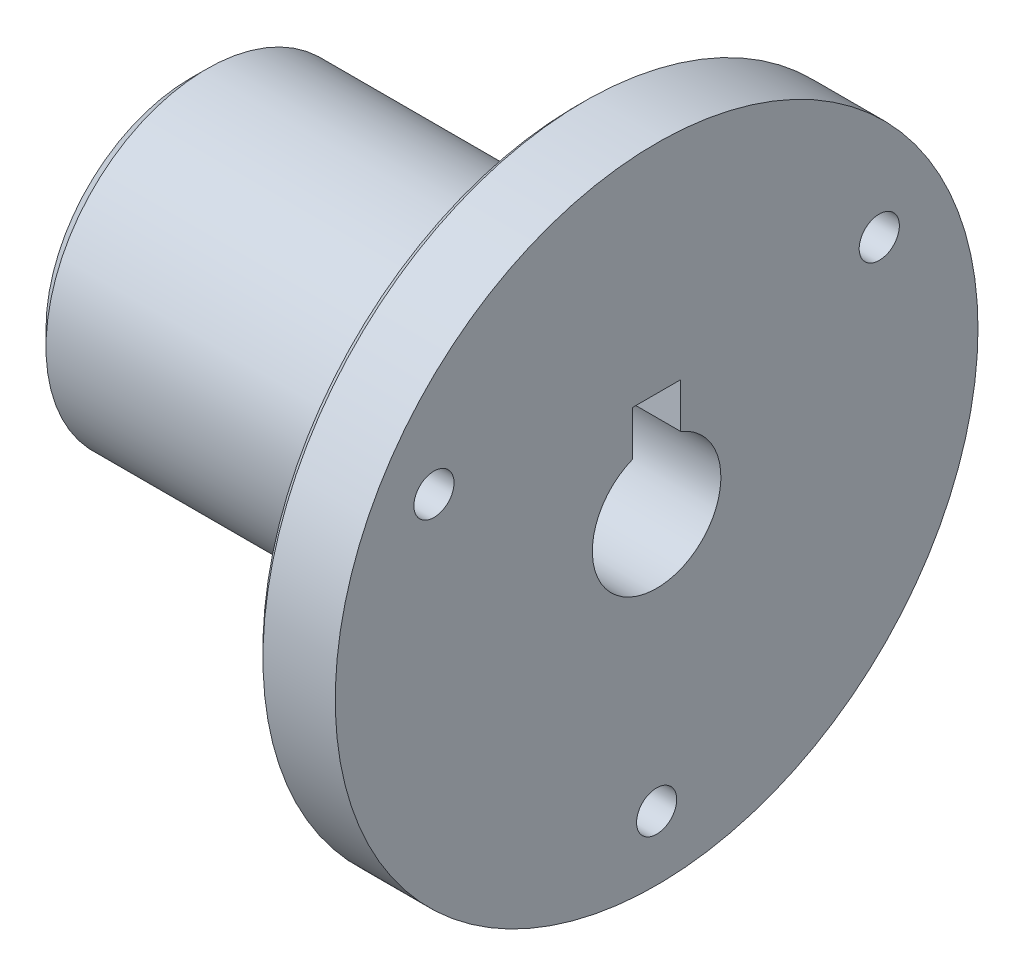
SolidWorks part; units mm, degrees
ref_plane "Front" through (0, 0, 0) normal (0, 0, 1) x (1, 0, 0)
ref_plane "Top" through (0, 0, 0) normal (0, 1, 0) x (1, 0, 0)
ref_plane "Right" through (0, 0, 0) normal (1, 0, 0) x (0, 0, -1)
sketch "草图1" plane through (0, 0, 0) normal (1, 0, 0) x (0, 0, -1)
  line L0 (-1.5, 6) -> (-1.5, 6.5)
  line L1 (0, 6) -> (-1.5, 6) construction
  line L2 (-1.5, 6) -> (-1.5, 3.7081)
  line L3 (0, 6) -> (1.5, 6) construction
  line L4 (1.5, 6) -> (1.5, 3.7081)
  line L5 (-1.5, 6.5) -> (1.5, 6.5)
  line L6 (1.5, 6.5) -> (1.5, 6)
  arc A0 (-1.5, 3.7081) -> (1.5, 3.7081) centre (0, 0) ccw
  circle A1 centre (0, 0) radius 10
extrude "凸台-拉伸1" add sketch "草图1" along normal blind 24
sketch "草图2" plane through (24, 0, 0) normal (1, 0, 0) x (0, 0, -1)
  line L0 (0, 0) -> (13.8564, 8) construction
  line L1 (0, 0) -> (-13.8564, 8) construction
  line L2 (0, 0) -> (0, -16) construction
  circle A0 centre (0, 0) radius 16 construction
  circle A1 centre (0, 0) radius 20
extrude "凸台-拉伸2" add sketch "草图2" along normal blind 5
hole_wizard "M3x0.5 螺纹孔1" positions "草图3" profile "草图4" tap size "M3x0.5" standard "ANSI Metric"
sketch "草图3" plane through (29, 0, 0) normal (1, 0, 0) x (0, 0, -1)
  point P0 (-13.8564, 8)
  point P3 (13.8564, 8)
  point P6 (0, -16)
sketch "草图4" plane through (29, 8, 13.8564) normal (0, 1, 0) x (0, 0, -1)
  line L0 (0, 0) -> (0, 8.2511)
  line L1 (0, 8.2511) -> (1.25, 7.5)
  line L2 (1.25, 7.5) -> (1.25, 0)
  line L5 (1.25, 0) -> (0, 0)
  line L10 (0, 8.2511) -> (-1.25, 7.5) construction
  line L11 (0, -6.35) -> (0, 107.95) construction
  dimension "螺纹孔钻头直径" = 2.5
  dimension "螺纹孔钻头深度" = 7.5
  dimension "导头角度" = 118
cosmetic thread "孔螺蚊线1" parameters "D1"=6, "D2"=3
cosmetic thread "孔螺蚊线2" parameters "D1"=6, "D2"=3
cosmetic thread "孔螺蚊线3" parameters "D1"=6, "D2"=3
sketch "草图5" plane through (29, 0, 0) normal (1, 0, 0) x (0, 0, -1)
  line L0 (-1.5, 6.5) -> (-1.5, 3.7081)
  line L1 (-1.5, 6.5) -> (1.5, 6.5)
  line L2 (1.5, 6.5) -> (1.5, 3.7081)
  arc A0 (-1.5, 3.7081) -> (1.5, 3.7081) centre (0, 0) ccw
extrude "切除-拉伸1" cut sketch "草图5" against normal up to next
chamfer "倒角1" distance 0.5 angle 45 1 edges at (0, -4, 0)
chamfer "倒角2" distance 1 angle 45 1 edges at (0, 0, -10)
chamfer "倒角3" distance 0.5 angle 45 1 edges at (24, 0, -20)
chamfer "倒角4" distance 2 angle 45 1 edges at (24, 0, -10)
